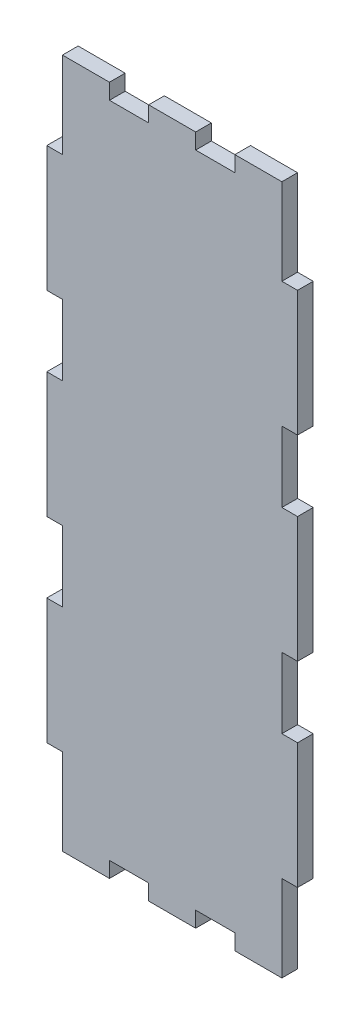
SolidWorks part; units mm, degrees
ref_plane "Front Plane" through (0, 0, 0) normal (0, 0, 1) x (1, 0, 0)
ref_plane "Top Plane" through (0, 0, 0) normal (0, 1, 0) x (1, 0, 0)
ref_plane "Right Plane" through (0, 0, 0) normal (1, 0, 0) x (0, 0, -1)
sketch "Sketch1" plane through (0, 0, 0) normal (0, 1, 0) x (1, 0, 0)
  line L1 (-28, 2) -> (28, 2)
  line L2 (-28, 2) -> (-28, -2)
  line L3 (-28, -2) -> (28, -2)
  line L4 (28, 2) -> (28, -2)
  line L5 (-28, 2) -> (28, -2) construction
  line L6 (-28, -2) -> (28, 2) construction
  point P0 (0, 0)
  dimension "D1" = 4
  dimension "D2" = 56
extrude "Boss-Extrude1" add sketch "Sketch1" along normal blind 168
sketch "Sketch2" plane through (0, 0, 2) normal (0, 0, 1) x (1, 0, 0)
  line L1 (-28, 0) -> (-32, 0)
  line L2 (-28, 0) -> (-28, 18)
  line L3 (-28, 18) -> (-32, 18)
  line L4 (-32, 0) -> (-32, 18)
  dimension "D1" = 4
  dimension "D2" = 18
extrude "Boss-Extrude3" [suppressed] add sketch "Sketch2" against normal through all contours L2 L1 L4 L3
pattern_linear "LPattern1" [suppressed] count 4 spacing 54
mirror "Mirror1" [suppressed] about plane through (0, 0, 0) normal (1, 0, 0)
sketch "Sketch3" plane through (0, 0, 2) normal (0, 0, 1) x (1, 0, 0)
  line L0 (-28, 18) -> (-32, 18)
  line L1 (-32, 18) -> (-32, 50)
  line L2 (-32, 50) -> (-28, 50)
  line L3 (-28, 50) -> (-28, 18)
  line L4 (-28, 168) -> (-28, 0) construction
  line L5 (-28, 0) -> (28, 0) construction
  point P8 (-31.75, 18.6428)
  point P11 (-31.75, 18)
  dimension "D1" = 18
  dimension "D2" = 4
  dimension "D3" = 32
extrude "Boss-Extrude4" add sketch "Sketch3" against normal through all
pattern_linear "LPattern2" count 3 spacing 50 along (0, 1, 0) of "Boss-Extrude4"
mirror "Mirror2" about plane through (0, 0, 0) normal (1, 0, 0) of "LPattern2", "Boss-Extrude4"
sketch "Sketch4" plane through (0, 0, 2) normal (0, 0, 1) x (1, 0, 0)
  line L1 (-28, 168) -> (-16, 168)
  line L2 (-28, 168) -> (-28, 172)
  line L3 (-28, 172) -> (-16, 172)
  line L4 (-16, 168) -> (-16, 172)
  line L12 (-32, 84) -> (32, 84) construction
  line L13 (-32, 100) -> (-32, 68) construction
  line L14 (32, 100) -> (32, 68) construction
  line L27 (6, 168) -> (6, 172)
  line L28 (-6, 172) -> (6, 172)
  line L29 (-6, 168) -> (-6, 172)
  line L30 (-6, 168) -> (6, 168)
  line L31 (28, 168) -> (28, 172)
  line L32 (16, 172) -> (28, 172)
  line L33 (16, 168) -> (16, 172)
  line L34 (16, 168) -> (28, 168)
  dimension "D1" = 12
  dimension "D2" = 4
  dimension "D4" = 10
  dimension "D3" = 3
extrude "Boss-Extrude5" add sketch "Sketch4" against normal through all
ref_plane "Plane1" through (0, 84, 0) normal (0, 1, 0) x (1, 0, 0)
mirror "Mirror3" about plane through (0, 84, 0) normal (0, 1, 0) of "Boss-Extrude5"
